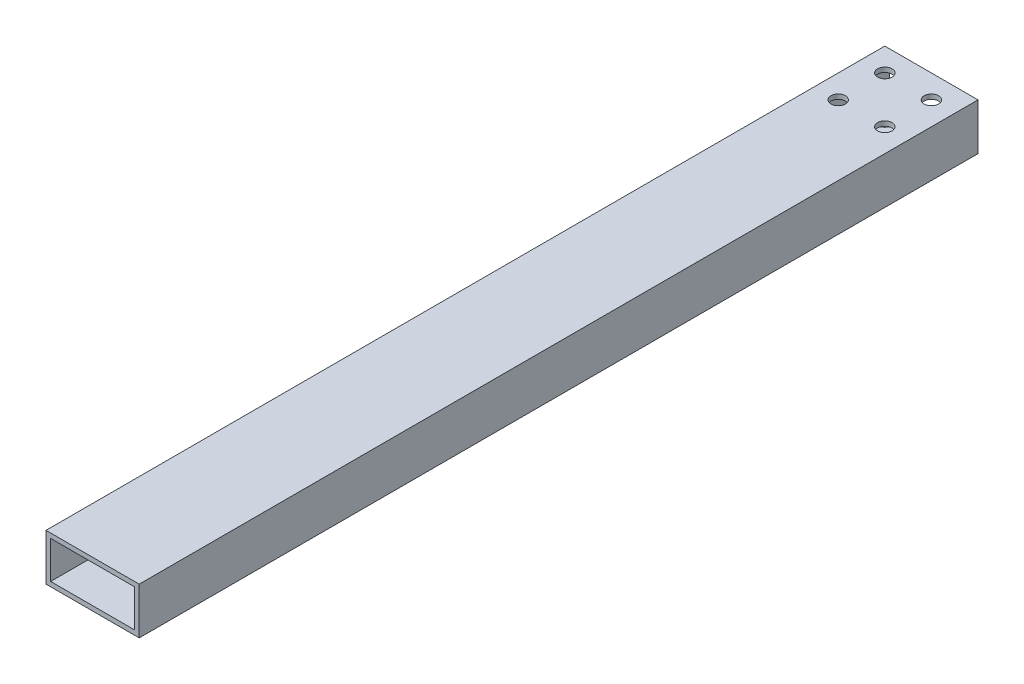
SolidWorks part; units mm, degrees
material "Thornel Mat VMA"
ref_plane "前视基准面" through (0, 0, 0) normal (0, 0, 1) x (1, 0, 0)
ref_plane "上视基准面" through (0, 0, 0) normal (0, 1, 0) x (1, 0, 0)
ref_plane "右视基准面" through (0, 0, 0) normal (1, 0, 0) x (0, 0, -1)
other "Configuration Table"
sketch "草图1" plane through (0, 0, 0) normal (0, 0, 1) x (1, 0, 0)
  line L0 (1, 1) -> (1, 9)
  line L1 (0, 0) -> (20, 0)
  line L2 (0, 0) -> (0, 10)
  line L3 (0, 10) -> (20, 10)
  line L4 (20, 0) -> (20, 10)
  line L5 (1, 9) -> (19, 9)
  line L6 (19, 1) -> (19, 9)
  line L7 (1, 1) -> (19, 1)
  dimension "D1" = 10
  dimension "D2" = 20
  dimension "D3" = 1
extrude "凸台-拉伸1" add sketch "草图1" along normal blind 180
sketch "草图2" plane through (0, 0, 0) normal (0, -1, 0) x (1, 0, 0)
  line L0 (0, 180) -> (0, 0) construction
  line L1 (0, 0) -> (20, 0) construction
  circle A0 centre (5, 5) radius 1.55
  circle A1 centre (15, 5) radius 1.55
  circle A2 centre (15, 15) radius 1.55
  circle A3 centre (5, 15) radius 1.55
  dimension "D2" = 3.1
  dimension "D1" = 5
  dimension "D3" = 5
  dimension "D4" = 2
  dimension "D5" = 2
extrude "切除-拉伸1" cut sketch "草图2" against normal through all
